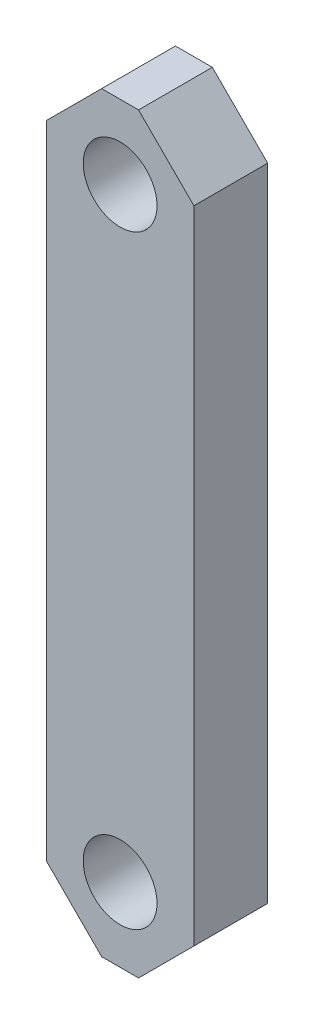
SolidWorks part; units mm, degrees
ref_plane "Front" through (0, 0, 0) normal (0, 0, 1) x (1, 0, 0)
ref_plane "Top" through (0, 0, 0) normal (0, 1, 0) x (1, 0, 0)
ref_plane "Right" through (0, 0, 0) normal (1, 0, 0) x (0, 0, -1)
sketch "Sketch1" plane through (0, 0, 0) normal (0, 0, 1) x (1, 0, 0)
  line L0 (0, 129.3812) -> (0, -129.3812) construction
  line L1 (-25.4, 129.3812) -> (25.4, 129.3812)
  line L2 (-25.4, 129.3812) -> (-25.4, -129.3812)
  line L3 (-25.4, -129.3812) -> (25.4, -129.3812)
  line L4 (25.4, 129.3812) -> (25.4, -129.3812)
  line L5 (-25.4, 0) -> (25.4, 0) construction
  circle A0 centre (0, 103.9813) radius 12.7
  circle A1 centre (0, -103.9813) radius 12.7
  dimension "D4" = 25.4
  dimension "D1" = 50.8
  dimension "D2" = 207.9625
  dimension "D3" = 25.4
extrude "Extrude1" add sketch "Sketch1" along normal mid plane 25.4
sketch "Sketch2" plane through (0, 0, 12.7) normal (0, 0, 1) x (1, 0, 0)
  line L0 (-6.35, 129.3812) -> (-25.4, 110.3313)
  line L1 (25.4, 129.3812) -> (-25.4, 129.3812) construction
  line L2 (-25.4, 129.3812) -> (-25.4, -129.3812) construction
  line L3 (-25.4, 110.3313) -> (-25.4, 129.3812)
  line L4 (-25.4, 129.3812) -> (-6.35, 129.3812)
  line L5 (6.35, 129.3812) -> (25.4, 110.3313)
  line L6 (25.4, 110.3313) -> (25.4, 129.3812)
  line L7 (25.4, 129.3812) -> (6.35, 129.3812)
  line L8 (-25.4, -110.3313) -> (-6.35, -129.3812)
  line L9 (-25.4, -129.3812) -> (25.4, -129.3812) construction
  line L10 (-6.35, -129.3812) -> (-25.4, -129.3812)
  line L11 (-25.4, -129.3812) -> (-25.4, -110.3313)
  line L12 (25.4, -110.3313) -> (25.4, -129.3812)
  line L13 (25.4, -129.3812) -> (25.4, 129.3812) construction
  line L14 (25.4, -129.3812) -> (6.35, -129.3812)
  line L15 (6.35, -129.3812) -> (25.4, -110.3313)
  dimension "D1" = 19.05
extrude "Cut-Extrude1" cut sketch "Sketch2" against normal through all
